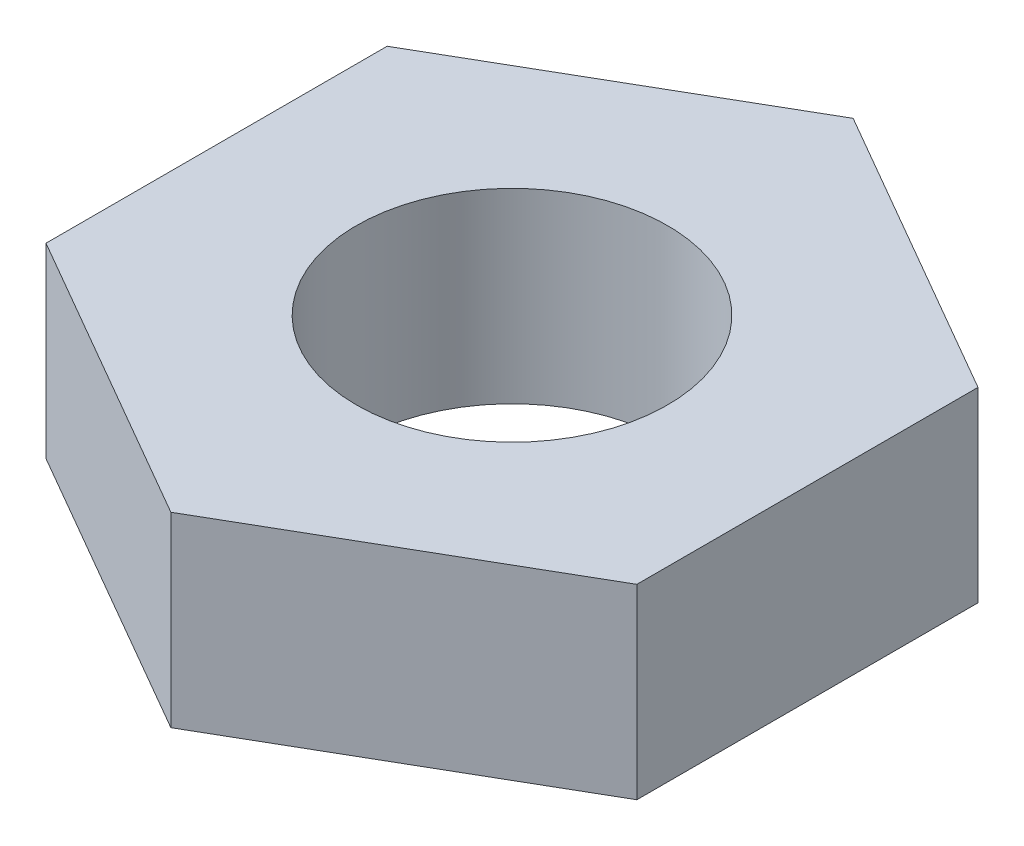
SolidWorks part; units mm, degrees
ref_plane "Alzado" through (0, 0, 0) normal (0, 0, 1) x (1, 0, 0)
ref_plane "Planta" through (0, 0, 0) normal (0, 1, 0) x (1, 0, 0)
ref_plane "Vista lateral" through (0, 0, 0) normal (1, 0, 0) x (0, 0, -1)
sketch "Croquis1" plane through (0, 0, 0) normal (0, 1, 0) x (1, 0, 0)
  line L1 (0, 5.4848) -> (-4.75, 2.7424)
  line L2 (-4.75, 2.7424) -> (-4.75, -2.7424)
  line L3 (-4.75, -2.7424) -> (0, -5.4848)
  line L4 (0, -5.4848) -> (4.75, -2.7424)
  line L5 (4.75, -2.7424) -> (4.75, 2.7424)
  line L6 (4.75, 2.7424) -> (0, 5.4848)
  circle A0 centre (0, 0) radius 2.5
  circle A1 centre (0, 0) radius 4.75 construction
  dimension "D1" = 5
  dimension "D2" = 9.5
extrude "Saliente-Extruir1" add sketch "Croquis1" along normal blind 3
